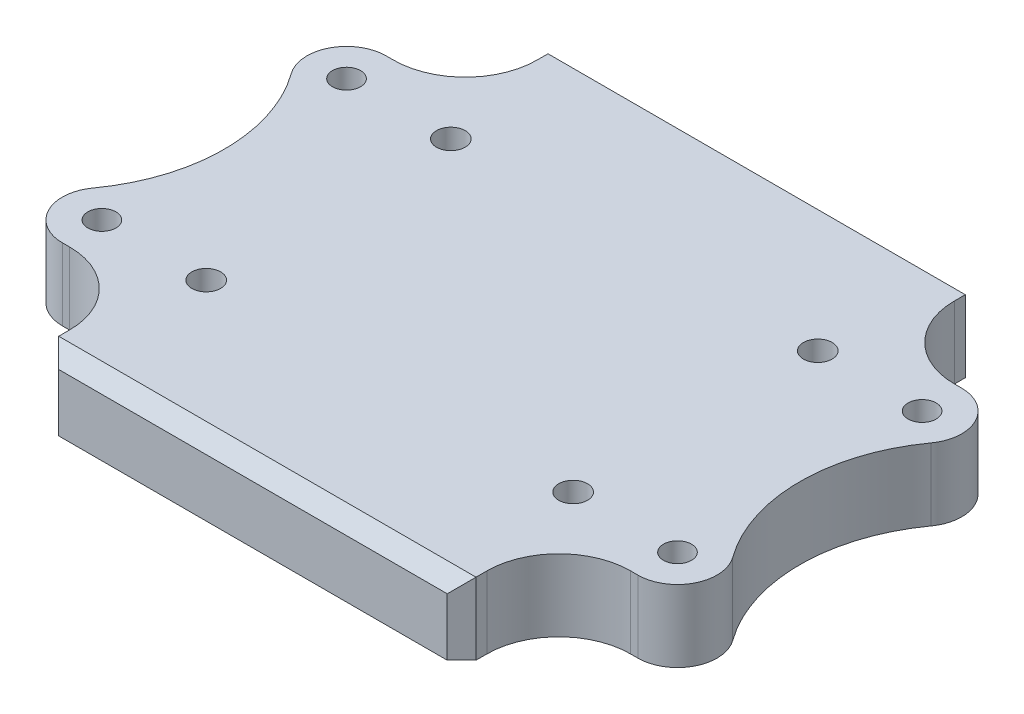
SolidWorks part; units mm, degrees
ref_plane "Front Plane" through (0, 0, 0) normal (0, 0, 1) x (1, 0, 0)
ref_plane "Top Plane" through (0, 0, 0) normal (0, 1, 0) x (1, 0, 0)
ref_plane "Right Plane" through (0, 0, 0) normal (1, 0, 0) x (0, 0, -1)
ref_plane "Plane1" through (0, -10, 0) normal (0, -1, 0) x (1, 0, 0)
sketch "Sketch1" plane through (0, -10, 0) normal (0, -1, 0) x (1, 0, 0)
  line L0 (-40, -22.5) -> (40, -22.5)
  line L1 (40, 22.5) -> (-40, 22.5)
  arc A0 (40, -22.5) -> (44.4577, -13.7784) centre (40, -17) ccw
  arc A1 (44.4577, -13.7784) -> (44.4577, 13.7784) centre (63.5227, 0) cw
  arc A2 (44.4577, 13.7784) -> (40, 22.5) centre (40, 17) ccw
  arc A3 (-40, 22.5) -> (-44.4577, 13.7784) centre (-40, 17) ccw
  arc A4 (-44.4577, 13.7784) -> (-44.4577, -13.7784) centre (-63.5227, 0) cw
  arc A5 (-44.4577, -13.7784) -> (-40, -22.5) centre (-40, -17) ccw
extrude "Boss-Extrude1" add sketch "Sketch1" against normal blind 10
sketch "Sketch2" plane through (0, 0, -22.5) normal (0, 0, -1) x (-1, 0, 0)
  line L0 (-29, -10) -> (-29, 0)
  line L1 (-29, 0) -> (29, 0)
  line L2 (29, 0) -> (29, -10)
  line L3 (29, -10) -> (-29, -10)
extrude "Boss-Extrude2" add sketch "Sketch2" along normal blind 13.5
sketch "Sketch3" plane through (0, 0, 22.5) normal (0, 0, 1) x (1, 0, 0)
  line L0 (29, -10) -> (-29, -10)
  line L1 (-29, -10) -> (-29, 0)
  line L2 (-29, 0) -> (29, 0)
  line L3 (29, 0) -> (29, -10)
extrude "Boss-Extrude3" add sketch "Sketch3" along normal blind 13.5
hole_wizard "Ø4.0 (4) Diameter Hole1" positions "Sketch5" profile "Sketch4" hole size "Ø4.0" standard "ANSI Metric"
sketch "Sketch5" plane through (0, 0, 0) normal (0, 1, 0) x (1, 0, 0)
  point P0 (-25.5, -17)
  point P1 (-25.5, 17)
  point P2 (25.5, 17)
  point P3 (25.5, -17)
sketch "Sketch4" plane through (-25.5, 0, 17) normal (1, 0, 0) x (0, 0, 1)
  line L0 (0, 0) -> (0, 10)
  line L1 (0, 10) -> (2, 10)
  line L2 (2, 10) -> (2, 0)
  line L5 (2, 0) -> (0, 0)
  line L11 (0, -6.35) -> (0, 107.95) construction
  dimension "Thru Hole Dia." = 4
  dimension "Thru Hole Depth" = 10
hole_wizard "Ø3.9 (3.9) Diameter Hole1" positions "Sketch7" profile "Sketch6" hole size "Ø3.9" standard "ANSI Metric"
sketch "Sketch7" plane through (0, -10, 0) normal (0, -1, 0) x (-1, 0, 0)
  point P0 (40, 17)
  point P1 (-40, 17)
  point P2 (-40, -17)
  point P3 (40, -17)
sketch "Sketch6" plane through (-40, -10, -17) normal (1, 0, 0) x (0, 0, -1)
  line L0 (0, 0) -> (0, 10)
  line L1 (0, 10) -> (1.95, 10)
  line L2 (1.95, 10) -> (1.95, 0)
  line L5 (1.95, 0) -> (0, 0)
  line L11 (0, -6.35) -> (0, 107.95) construction
  dimension "Thru Hole Dia." = 3.9
  dimension "Thru Hole Depth" = 10
chamfer "Chamfer1" distance 1.5 angle 45 4 edges at (40, -10, 15.05) (-40, -10, -18.95) (40, -10, -18.95) (-40, -10, 15.05)
chamfer "Chamfer2" distance 2 angle 45 6 edges at (-29, -5, 36) (29, -5, 36) (0, 0, 36) (29, -5, -36) (0, 0, -36) (-29, -5, -36)
fillet "Fillet1" radius 10 4 edges at (-29, -5, -22.5) (29, -5, 22.5) (29, -5, -22.5) (-29, -5, 22.5)
